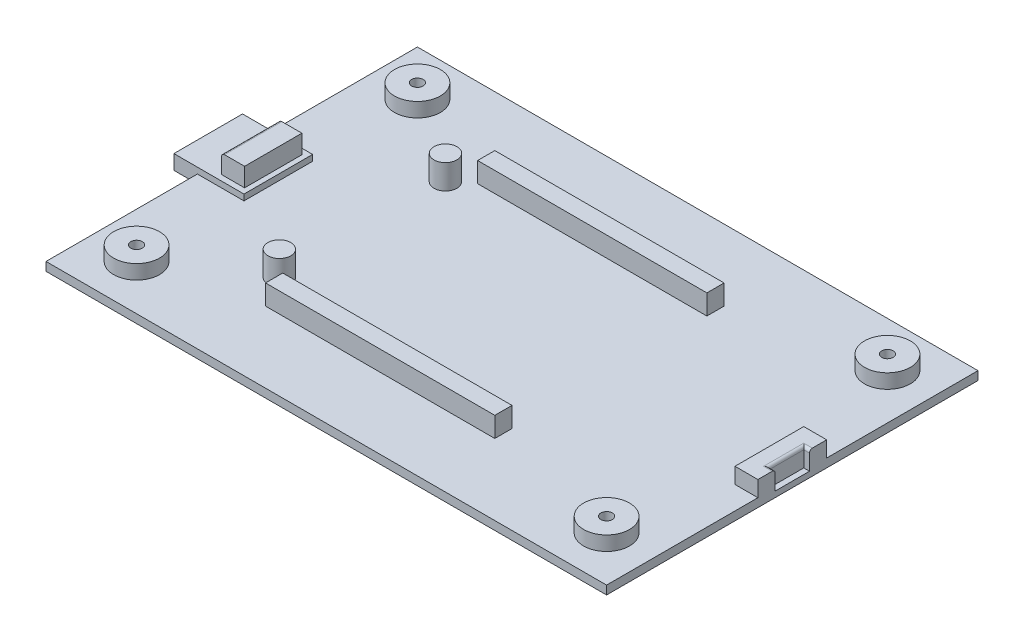
SolidWorks part; units mm, degrees
material "PLA"
ref_plane "前视基准面" through (0, 0, 0) normal (0, 0, 1) x (1, 0, 0)
ref_plane "上视基准面" through (0, 0, 0) normal (0, 1, 0) x (1, 0, 0)
ref_plane "右视基准面" through (0, 0, 0) normal (1, 0, 0) x (0, 0, -1)
other "Configuration Table"
sketch "草图1" plane through (0, 0, 0) normal (0, 1, 0) x (1, 0, 0)
  line L0 (-51.7144, -9.4544) -> (-55.8167, -9.4544)
  line L1 (-51.7144, 16.9583) -> (46.0856, 16.9583)
  line L2 (-51.7144, 16.9583) -> (-51.7144, -9.4544)
  line L3 (-51.7144, -47.8417) -> (46.0856, -47.8417)
  line L4 (46.0856, 16.9583) -> (46.0856, -47.8417)
  line L5 (-51.7144, 16.9583) -> (46.0856, -47.8417) construction
  line L6 (-51.7144, -47.8417) -> (46.0856, 16.9583) construction
  line L7 (-55.8167, -9.4544) -> (-55.8167, -21.429)
  line L8 (-51.8144, -9.3544) -> (-51.8144, 17.0583) construction
  line L9 (46.1856, -47.9417) -> (-51.8144, -47.9417) construction
  line L10 (-55.8167, -21.429) -> (-51.7144, -21.429)
  line L11 (-51.7144, -21.429) -> (-51.7144, -47.8417)
  line L12 (-51.8144, -9.3544) -> (-55.9167, -9.3544) construction
  line L13 (-55.9167, -21.529) -> (-51.8144, -21.529) construction
  line L14 (-55.9167, -9.3544) -> (-55.9167, -21.529) construction
  point P0 (0, 0)
  dimension "D1" = 97.8
  dimension "D2" = 64.8
  dimension "D3" = 0.1
  dimension "D4" = 0.1
  dimension "D5" = 0.1
  dimension "D6" = 0.1
  dimension "D7" = 0.1
extrude "凸台-拉伸1" add sketch "草图1" along normal blind 1.5
sketch "草图2" plane through (0, 0, 0) normal (0, -1, 0) x (1, 0, 0)
  line L0 (-51.7144, 47.8417) -> (46.0856, 47.8417) construction
  line L1 (-2.8144, -16.9583) -> (-2.8144, 10.2547) construction
  line L2 (-51.7144, 21.429) -> (-51.7144, 47.8417) construction
  line L3 (46.0856, -16.9583) -> (-51.7144, -16.9583) construction
  circle A0 centre (-43.8144, -9.0583) radius 5
  circle A1 centre (-43.8144, 39.9417) radius 5
  circle A4 centre (-43.8144, -9.0583) radius 4 construction
  circle A5 centre (38.1856, 39.9417) radius 5
  circle A6 centre (38.1856, -9.0583) radius 5
  dimension "D1" = 10
  dimension "D2" = 10
  dimension "D5" = 7.9
  dimension "D6" = 7.9
extrude "防滑切除-拉伸1" cut sketch "草图2" against normal blind 0.5
sketch "草图11" plane through (0, 0, 0) normal (0, -1, 0) x (1, 0, 0)
  line L0 (-55.8167, 9.4544) -> (-55.8167, 21.429) construction
  line L1 (-43.5867, 9.4544) -> (-55.8167, 9.4544)
  line L2 (-43.5867, 9.4544) -> (-43.5867, 21.429)
  line L3 (-43.5867, 21.429) -> (-55.8167, 21.429)
  line L4 (-55.8167, 9.4544) -> (-55.8167, 21.429)
  line L6 (-55.8167, 21.429) -> (-51.7144, 21.429) construction
  line L8 (-51.7144, 9.4544) -> (-55.8167, 9.4544) construction
  line L9 (-48.5867, 14.1953) -> (-48.5867, 16.6882) construction
  line L10 (-25.9144, 32.929) -> (-25.9144, -2.0456) construction
  line L11 (-48.389, 32.929) -> (-25.9144, 32.929) construction
  line L13 (-25.9144, 15.4417) -> (-37.5911, 15.4417) construction
  circle A0 centre (-28.9144, 29.929) radius 2
  circle A1 centre (-28.9144, 0.9544) radius 2
  dimension "D2" = 4
  dimension "D4" = 3
  dimension "D1" = 5
  dimension "D3" = 3
extrude "充电板档板凸台-拉伸5" add sketch "草图11" against normal up to surface (2.54 mm away)
sketch "草图13" plane through (0, 0, 0) normal (0, -1, 0) x (1, 0, 0)
  line L1 (-48.389, 32.929) -> (-25.9144, 32.929) construction
  line L2 (-25.9144, 32.929) -> (-25.9144, -2.0456) construction
  line L3 (-25.9144, 15.4417) -> (-36.6222, 15.4417) construction
  line L4 (-48.5667, 14.1953) -> (-48.5667, 16.6882) construction
  line L5 (-48.4667, 10.4417) -> (-44.4667, 10.4417)
  line L6 (-48.4667, 10.4417) -> (-48.4667, 20.4417)
  line L7 (-48.4667, 20.4417) -> (-44.4667, 20.4417)
  line L8 (-44.4667, 10.4417) -> (-44.4667, 20.4417)
  circle A1 centre (-28.9144, 29.929) radius 2
  circle A2 centre (-28.9144, 0.9544) radius 2
  dimension "D1" = 4
  dimension "D2" = 3
  dimension "D3" = 3
  dimension "D4" = 4
  dimension "D5" = 10
  dimension "D6" = 0.1
extrude "TypeC支撑凸台-拉伸2" add sketch "草图13" against normal up to surface (5.8 mm away)
sketch "草图14" plane through (0, 0, 0) normal (0, -1, 0) x (1, 0, 0)
  line L1 (45.0856, 12.4417) -> (45.0856, 18.4417)
  line L2 (45.0856, 18.4417) -> (46.0856, 18.4417)
  line L3 (46.0856, 18.4417) -> (46.0856, 21.4417)
  line L4 (46.0856, 47.8417) -> (46.0856, -16.9583) construction
  line L5 (46.0856, 21.4417) -> (42.0856, 21.4417)
  line L6 (42.0856, 21.4417) -> (42.0856, 9.4417)
  line L7 (42.0856, 9.4417) -> (46.0856, 9.4417)
  line L8 (46.0856, 9.4417) -> (46.0856, 12.4417)
  line L9 (46.0856, 12.4417) -> (45.0856, 12.4417)
  line L10 (46.0856, 15.4417) -> (41.9652, 15.4417) construction
  line L11 (46.1856, 18.3417) -> (45.1856, 18.3417) construction
  line L12 (45.1856, 18.3417) -> (45.1856, 12.9417) construction
  dimension "D1" = 0.1
  dimension "D2" = 0.1
  dimension "D3" = 3
  dimension "D4" = 3
  dimension "D5" = 3
extrude "LED限位凸台-拉伸3" add sketch "草图14" along normal up to surface (2.75 mm away) from surface
fillet "LED限位圆角1" radius 0.5 4 edges at (-48.4667, 5.8, 15.4417) (45.0856, 4.25, 15.4417) (45.5856, 4.25, 18.4417) (45.5856, 4.25, 12.4417)
sketch "草图15" plane through (0, 0, 0) normal (0, -1, 0) x (1, 0, 0)
  circle A0 centre (-43.8144, -9.0583) radius 2
  circle A1 centre (-43.8144, 39.9417) radius 2
  circle A2 centre (38.1856, -9.0583) radius 2
  circle A3 centre (38.1856, 39.9417) radius 2
  circle A4 centre (38.1856, -9.0583) radius 5 construction
  circle A5 centre (38.1856, 39.9417) radius 5 construction
  circle A6 centre (-43.8144, -9.0583) radius 5 construction
  circle A7 centre (-43.8144, 39.9417) radius 5 construction
  dimension "D1" = 4
  dimension "D2" = 4
  dimension "D3" = 4
  dimension "D4" = 4
extrude "螺丝孔位切除-拉伸2" cut sketch "草图15" against normal up to next
sketch "草图16" plane through (0, 0, 0) normal (0, -1, 0) x (1, 0, 0)
  circle A0 centre (38.1856, -9.0583) radius 1
  circle A1 centre (38.1856, 39.9417) radius 1
  circle A2 centre (-43.8144, -9.0583) radius 1
  circle A3 centre (-43.8144, -9.0583) radius 5 construction
  circle A8 centre (-43.8144, 39.9417) radius 5 construction
  circle A9 centre (38.1856, -9.0583) radius 5 construction
  circle A10 centre (38.1856, 39.9417) radius 5 construction
  circle A12 centre (38.1856, -9.0583) radius 4
  circle A13 centre (38.1856, 39.9417) radius 4
  circle A14 centre (-43.8144, -9.0583) radius 4
  circle A15 centre (-43.8144, 39.9417) radius 4
  circle A16 centre (-43.8144, 39.9417) radius 1
  dimension "D3" = 8
  dimension "D4" = 8
  dimension "D5" = 8
  dimension "D6" = 8
  dimension "D1" = 3
  dimension "D2" = 3
extrude "螺丝孔凸台-拉伸4" add sketch "草图16" along normal up to surface (2.5 mm away) from surface
sketch "草图17" plane through (0, 0, 0) normal (0, -1, 0) x (1, 0, 0)
  line L0 (45.0856, 12.4417) -> (46.1856, 12.4417) construction
  line L1 (45.0856, 18.4417) -> (45.0856, 12.4417) construction
  line L2 (46.1856, 18.4417) -> (45.0856, 18.4417) construction
  line L3 (45.0856, 12.4417) -> (46.0856, 12.4417)
  line L4 (45.0856, 18.4417) -> (45.0856, 12.4417)
  line L5 (46.0856, 18.4417) -> (45.0856, 18.4417)
  line L6 (46.0856, 12.4417) -> (46.0856, 18.4417)
  line L7 (46.0856, 47.8417) -> (46.0856, -16.9583) construction
extrude "LED灯嵌入切除-拉伸2" cut sketch "草图17" along normal blind 0.5 from surface at -1.5 starting at face at (-43.8144, 1.5, 43.9417)
sketch "草图18" plane through (0, 1.5, 0) normal (0, 1, 0) x (1, 0, 0)
  line L0 (-25.8144, 0.5583) -> (-25.8144, -1.4417) construction
  line L1 (14.1856, 4.5583) -> (-25.8144, 4.5583)
  line L2 (14.1856, 4.5583) -> (14.1856, 1.5583)
  line L4 (-25.8144, 4.5583) -> (-25.8144, 1.5583)
  line L7 (14.1856, -32.4417) -> (-25.8144, -32.4417)
  line L8 (14.1856, -32.4417) -> (14.1856, -35.4417)
  line L9 (14.1856, -35.4417) -> (-25.8144, -35.4417)
  line L10 (-25.8144, -32.4417) -> (-25.8144, -35.4417)
  line L11 (14.1856, -31.4417) -> (14.1856, -29.4417) construction
  line L15 (14.1856, 1.5583) -> (-25.8144, 1.5583)
  dimension "D1" = 3
  dimension "D2" = 3
extrude "散热板支撑凸台-拉伸2" add sketch "草图18" along normal up to surface (3.5 mm away)
